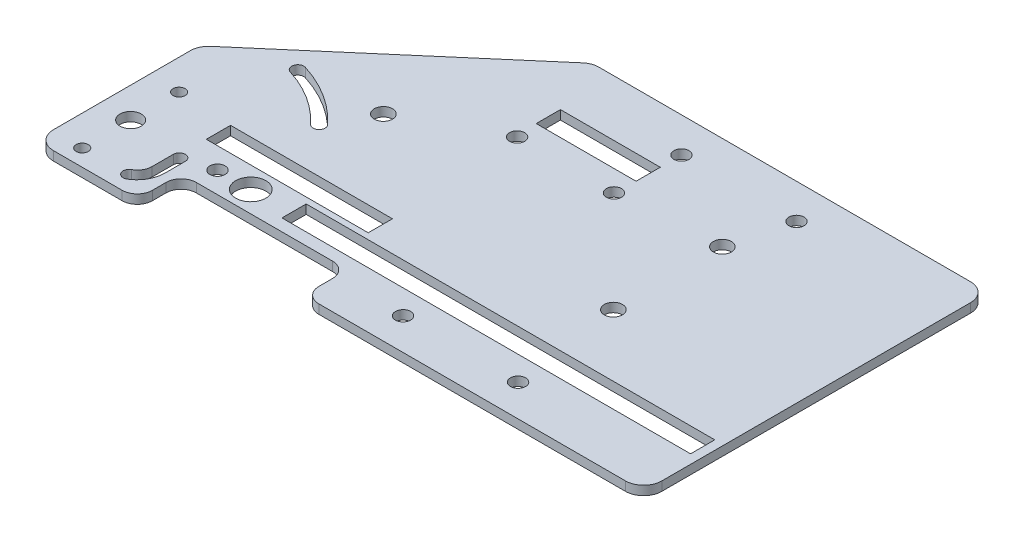
SolidWorks part; units mm, degrees
ref_plane "前视基准面" through (0, 0, 0) normal (0, 0, 1) x (1, 0, 0)
ref_plane "上视基准面" through (0, 0, 0) normal (0, 1, 0) x (1, 0, 0)
ref_plane "右视基准面" through (0, 0, 0) normal (1, 0, 0) x (0, 0, -1)
sketch "草图1" plane through (0, 0, 0) normal (0, 1, 0) x (1, 0, 0)
  line L0 (-81, 76.8404) -> (-71, 89.1596) construction
  line L1 (0, 0) -> (-220, 0)
  line L2 (-210, 21.5) -> (-177.5673, 51.3251) construction
  line L3 (0, 114) -> (-220, 114)
  line L4 (-220, 0) -> (-220, 114)
  line L5 (-193.1579, 18.7437) -> (-193.1579, 11.7437)
  line L6 (-189.1579, 12.0351) -> (-189.1579, 18.7437)
  line L7 (-157, 26.5) -> (-22, 26.5)
  line L8 (-157, 18.5) -> (-22, 18.5)
  line L9 (-157, 26.5) -> (-157, 18.5)
  line L10 (0, 0) -> (0, 114)
  line L11 (-138.5, 28.5) -> (-192, 28.5)
  line L12 (-138.5, 28.5) -> (-138.5, 36.5)
  line L13 (-138.5, 36.5) -> (-192, 36.5)
  line L14 (-22, 26.5) -> (-22, 18.5)
  line L15 (-192, 28.5) -> (-192, 36.5)
  line L16 (-196.825, 63.5456) -> (-210.0029, 21.5) construction
  line L17 (-142, 87.5) -> (-109, 87.5)
  line L18 (-142, 87.5) -> (-142, 95.5)
  line L19 (-142, 95.5) -> (-109, 95.5)
  line L20 (-109, 87.5) -> (-109, 95.5)
  line L21 (-210.0029, 21.5) -> (-210.0029, 67.1885) construction
  line L22 (-191.1579, 18.7437) -> (-191.1579, 11.7437) construction
  line L23 (-198.008, 11.7437) -> (-191.1579, 11.7437) construction
  line L24 (-198.01, 11.7437) -> (-194.725, 5.7299) construction
  line L25 (-198.01, 11.7437) -> (-198.01, 2.871) construction
  circle A0 centre (-71, 102.5) radius 2.5
  circle A1 centre (-109, 102.5) radius 2.5
  circle A2 centre (-141.3129, 80.5) radius 2.5
  circle A3 centre (-109.3129, 80.5) radius 2.5
  circle A4 centre (-109, 10.5) radius 2.5
  circle A5 centre (-71, 10.5) radius 2.5
  circle A6 centre (-76, 47) radius 3
  circle A7 centre (-76, 83) radius 3
  circle A8 centre (-170, 65) radius 3
  circle A9 centre (-170.3129, 21.5) radius 5
  circle A10 centre (-181.3129, 21.5) radius 2.5
  circle A11 centre (-210.0029, 37.5) radius 2
  circle A12 centre (-210.0029, 5.5) radius 2
  arc A14 (-194.6031, 5.7997) -> (-191.1579, 11.7437) centre (-198.008, 11.7437) ccw construction
  arc A17 (-196.227, 65.4541) -> (-197.423, 61.6371) centre (-196.825, 63.5456) ccw
  arc A18 (-176.0952, 52.6789) -> (-196.227, 65.4541) centre (-210, 21.5) ccw
  arc A19 (-179.0395, 49.9713) -> (-197.423, 61.6371) centre (-210, 21.5) ccw
  arc A20 (-179.0395, 49.9713) -> (-176.0952, 52.6789) centre (-177.5673, 51.3251) ccw
  arc A21 (-193.1579, 11.7437) -> (-195.684, 7.4854) centre (-198.01, 11.7437) cw
  arc A22 (-195.684, 7.4854) -> (-193.6945, 4.0153) centre (-194.725, 5.7299) ccw
  arc A23 (-193.6945, 4.0153) -> (-189.1579, 12.0351) centre (-198.5148, 12.0351) ccw
  arc A24 (-189.1579, 18.7437) -> (-193.1579, 18.7437) centre (-191.1579, 18.7437) ccw
  circle A25 centre (-210.0029, 21.5) radius 3.5
  arc A27 (-177.5673, 51.3251) -> (-196.825, 63.5456) centre (-210, 21.5) ccw construction
  dimension "D3" = 5
  dimension "D4" = 5
  dimension "D5" = 5
  dimension "D6" = 5
  dimension "D7" = 5
  dimension "D8" = 5
  dimension "D9" = 6
  dimension "D10" = 6
  dimension "D11" = 6
  dimension "D12" = 10
  dimension "D13" = 5
  dimension "D14" = 4
  dimension "D15" = 4
  dimension "D28" = 39.69
  dimension "D39" = 7
  dimension "D43" = 44.0615
  dimension "D45" = 6.8501
  dimension "D46" = 4
  dimension "D1" = 220
  dimension "D2" = 114
  dimension "D16" = 63
  dimension "D17" = 8
  dimension "D18" = 18.5
  dimension "D19" = 135
  dimension "D20" = 8
  dimension "D21" = 28
  dimension "D22" = 28.5
  dimension "D23" = 53.5
  dimension "D24" = 87.5
  dimension "D25" = 8
  dimension "D26" = 78
  dimension "D27" = 33
  dimension "D29" = 38
  dimension "D30" = 10.5
  dimension "D31" = 111
  dimension "D32" = 92
  dimension "D33" = 22
  dimension "D34" = 0.3129
  dimension "D35" = 32
  dimension "D36" = 61
  dimension "D37" = 59
  dimension "D38" = 11
  dimension "D40" = 16
  dimension "D41" = 16
  dimension "D42" = 29.996
  dimension "D44" = 28.645
  dimension "D47" = 7
  dimension "D48" = 11.9949
  dimension "D49" = 9.7563
  dimension "D50" = 17.402
  dimension "D51" = 90
extrude "凸台-拉伸1" add sketch "草图1" along normal mid plane 3
sketch "草图2" plane through (0, 1.5, 0) normal (0, 1, 0) x (1, 0, 0)
  line L0 (-220, 0) -> (0, 0) construction
  line L1 (-186.3129, 14.5) -> (-131.3129, 14.5)
  line L2 (-186.3129, 14.5) -> (-186.3129, 0)
  line L3 (-186.3129, 0) -> (-131.3129, 0)
  line L4 (-131.3129, 14.5) -> (-131.3129, 0)
  dimension "D1" = 55
extrude "切除-拉伸1" cut sketch "草图2" against normal through all
fillet "圆角1" radius 5 4 edges at (-186.3129, 0, 0) (-186.3129, 0, -14.5) (-131.3129, 0, 0) (-131.3129, 0, -14.5)
sketch "草图3" plane through (0, 1.5, 0) normal (0, 1, 0) x (1, 0, 0)
  line L0 (-220, 54) -> (-150, 114)
  line L1 (-220, 114) -> (-220, 0) construction
  line L2 (0, 114) -> (-220, 114) construction
  line L3 (-150, 114) -> (-220, 114)
  line L4 (-220, 114) -> (-220, 54)
  line L5 (-22, 18.5) -> (-22, 26.5) construction
  line L6 (0, 0) -> (-19, 0)
  line L7 (0, 0) -> (0, 114)
  line L8 (0, 114) -> (-19, 114)
  line L9 (-19, 0) -> (-19, 114)
  dimension "D1" = 60
  dimension "D2" = 70
  dimension "D3" = 3
extrude "切除-拉伸2" cut sketch "草图3" against normal through all
fillet "圆角2" radius 6 5 edges at (-19, 0, -114) (-19, 0, 0) (-150, 0, -114) (-220, 0, -54) (-220, 0, 0)
